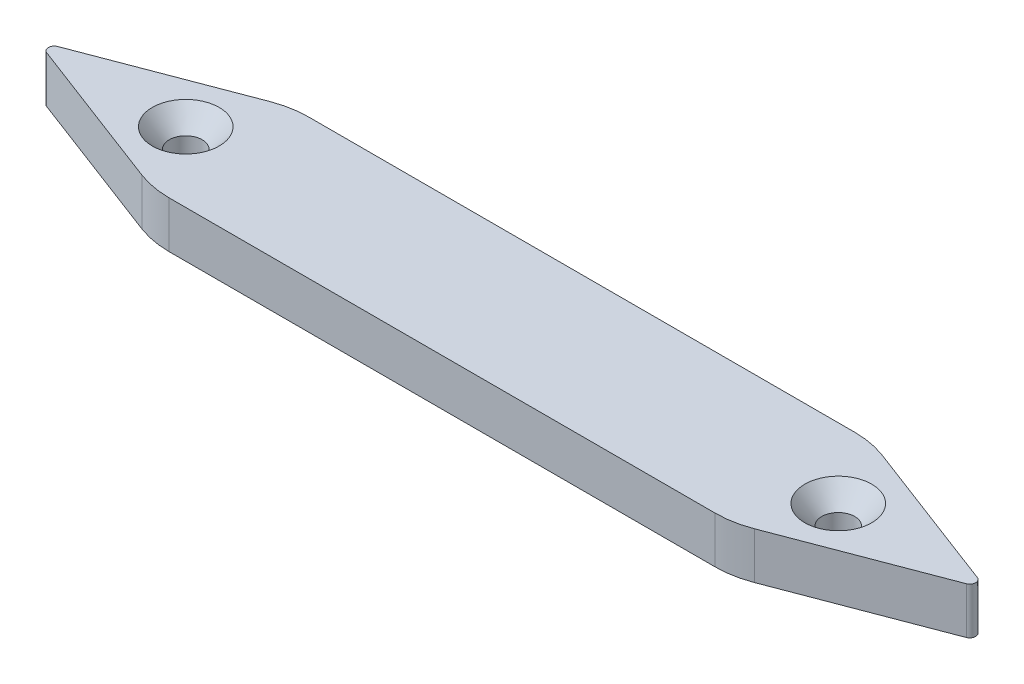
SolidWorks part; units mm, degrees
ref_plane "Front Plane" through (0, 0, 0) normal (0, 0, 1) x (1, 0, 0)
ref_plane "Top Plane" through (0, 0, 0) normal (0, 1, 0) x (1, 0, 0)
ref_plane "Right Plane" through (0, 0, 0) normal (1, 0, 0) x (0, 0, -1)
sketch "Sketch1" plane through (0, 0, 0) normal (0, 1, 0) x (1, 0, 0)
  line L0 (-119.3628, 0) -> (111.8082, 0) construction
  line L1 (0, 90.7812) -> (0, -92.2921) construction
  line L2 (37.205, 9.525) -> (-37.205, 9.525)
  line L3 (-41.7162, 8.6968) -> (-62.6498, 0.742)
  line L4 (37.205, -9.525) -> (-37.205, -9.525)
  line L5 (-41.7162, -8.6968) -> (-62.6498, -0.742)
  line L6 (41.7162, -8.6968) -> (62.6498, -0.742)
  line L7 (41.7162, 8.6968) -> (62.6498, 0.742)
  arc A0 (-37.205, 9.525) -> (-41.7162, 8.6968) centre (-37.205, -3.175) ccw
  arc A1 (-37.205, -9.525) -> (-41.7162, -8.6968) centre (-37.205, 3.175) cw
  arc A2 (-62.6498, -0.742) -> (-62.6498, 0.742) centre (-62.3679, 0) cw
  arc A3 (37.205, -9.525) -> (41.7162, -8.6968) centre (37.205, 3.175) ccw
  arc A4 (62.6498, -0.742) -> (62.6498, 0.742) centre (62.3679, 0) ccw
  arc A5 (37.205, 9.525) -> (41.7162, 8.6968) centre (37.205, -3.175) cw
  point P6 (-64.6024, 0)
  point P18 (0, -9.525)
  point P26 (0, 9.525)
  dimension "D1" = 12.7
  dimension "D2" = 0.7937
  dimension "D3" = 19.05
extrude "Boss-Extrude2" add sketch "Sketch1" along normal blind 22.225 and the other way blind 10
sketch "Sketch2" plane through (0, 0, 9.525) normal (0, 0, 1) x (1, 0, 0)
  line L0 (-37.205, 22.225) -> (37.205, 22.225) construction
  line L1 (-68.6771, 15.875) -> (84.4664, 15.875)
  line L2 (-68.6771, 15.875) -> (-68.6771, 9.525)
  line L3 (-68.6771, 9.525) -> (84.4664, 9.525)
  line L4 (84.4664, 15.875) -> (84.4664, 9.525)
  dimension "D1" = 6.35
  dimension "D2" = 6.35
extrude "Cut-Extrude1" cut sketch "Sketch2" against normal blind 4.7625
sketch "Sketch3" plane through (0, 0, -9.525) normal (0, 0, -1) x (-1, 0, 0)
  line L0 (-37.205, 22.225) -> (37.205, 22.225) construction
  line L1 (-67.7785, 15.875) -> (84.9799, 15.875)
  line L2 (-67.7785, 15.875) -> (-67.7785, 9.525)
  line L3 (-67.7785, 9.525) -> (84.9799, 9.525)
  line L4 (84.9799, 15.875) -> (84.9799, 9.525)
  dimension "D1" = 6.35
  dimension "D2" = 6.35
extrude "Cut-Extrude2" cut sketch "Sketch3" against normal blind 4.7625
fillet "Fillet3" radius 12.7 1 edges at (52.0695, 12.7, -4.7625)
fillet "Fillet4" radius 12.7 1 edges at (52.0695, 12.7, 4.7625)
fillet "Fillet5" radius 12.7 1 edges at (-52.0695, 12.7, 4.7625)
fillet "Fillet6" radius 12.7 1 edges at (-52.0695, 12.7, -4.7625)
sketch "Sketch12" plane through (0, 0, 0) normal (1, 0, 0) x (0, 0, -1)
  circle A0 centre (0, -168.402) radius 168.402
extrude "Cut-Extrude3" cut sketch "Sketch12" against normal blind 84.675 and the other way blind 94.675
sketch "Sketch19" plane through (0, 22.225, 0) normal (0, 1, 0) x (1, 0, 0)
  point P0 (-44.45, 0)
  point P1 (44.45, 0)
hole_wizard "CSK for #8 Flat Head Socket Cap Screw2" positions "Sketch21" profile "Sketch20" countersink size "#8" standard "ANSI Inch" end condition through all
sketch "Sketch21" plane through (0, 22.225, 0) normal (0, 1, 0) x (1, 0, 0)
  point P0 (-44.45, 0)
  point P3 (44.45, 0)
sketch "Sketch20" plane through (-44.45, 22.225, 0) normal (1, 0, 0) x (0, 0, 1)
  line L0 (0, 0) -> (0, 23.3241)
  line L1 (0, 23.3241) -> (2.2479, 23.3241)
  line L2 (2.2479, 23.3241) -> (2.2479, 2.659)
  line L3 (2.2479, 2.659) -> (4.5593, 0)
  line L5 (4.5593, 0) -> (0, 0)
  line L6 (-2.2479, 2.659) -> (-4.5593, 0) construction
  line L11 (0, -6.35) -> (0, 107.95) construction
  dimension "Thru Hole Dia." = 4.4958
  dimension "Thru Hole Depth" = 23.3241
  dimension "Near C'Sink Dia." = 9.1186
  dimension "Near C'Sink Angle" = 82
ref_plane "Plane6" through (0, 3.175, 0) normal (0, 1, 0) x (1, 0, 0)
ref_plane "Plane7" through (0, 9.525, 0) normal (0, 1, 0) x (1, 0, 0)
ref_plane "Plane8" through (0, 15.875, 0) normal (0, 1, 0) x (1, 0, 0)
sketch "Sketch24" plane through (0, 15.875, 0) normal (0, 1, 0) x (1, 0, 0)
  line L1 (-86.6807, 31.4582) -> (94.5544, 31.4582)
  line L2 (-86.6807, 31.4582) -> (-86.6807, -37.7971)
  line L3 (-86.6807, -37.7971) -> (94.5544, -37.7971)
  line L4 (94.5544, 31.4582) -> (94.5544, -37.7971)
extrude "Cut-Extrude5" cut sketch "Sketch24" against normal blind 84.675
